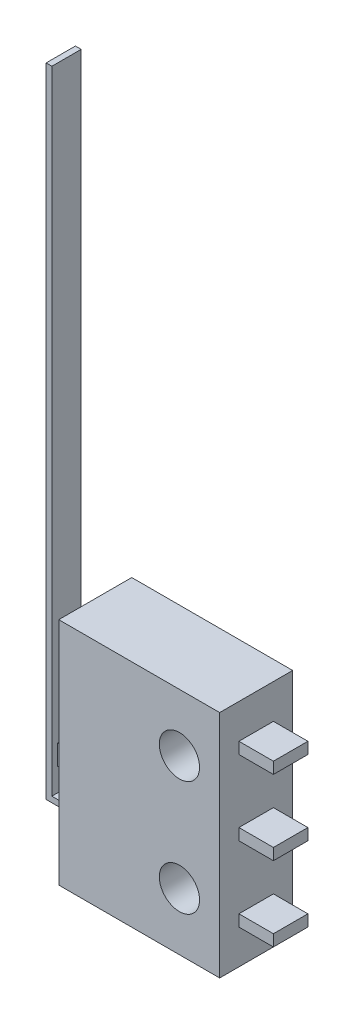
SolidWorks part; units mm, degrees
ref_plane "Front Plane" through (0, 0, 0) normal (0, 0, 1) x (1, 0, 0)
ref_plane "Top Plane" through (0, 0, 0) normal (0, 1, 0) x (1, 0, 0)
ref_plane "Right Plane" through (0, 0, 0) normal (1, 0, 0) x (0, 0, -1)
sketch "Sketch1" plane through (0, 0, 0) normal (0, 0, 1) x (1, 0, 0)
  line L1 (0, 0) -> (14, 0)
  line L2 (0, 0) -> (0, 20)
  line L3 (0, 20) -> (14, 20)
  line L4 (14, 0) -> (14, 20)
  dimension "D1" = 14
  dimension "D2" = 20
extrude "Boss-Extrude1" add sketch "Sketch1" against normal blind 6.35
sketch "Sketch2" plane through (0, 0, 0) normal (-1, 0, 0) x (0, 0, 1)
  line L0 (-6.35, 7) -> (0, 7) construction
  line L1 (-6.35, 20) -> (-6.35, 0) construction
  line L2 (0, 20) -> (0, 0) construction
  line L3 (-6.35, 0) -> (0, 0) construction
  line L5 (-4.45, 7) -> (-1.9, 7)
  line L6 (-4.45, 7) -> (-4.45, 8.7542)
  line L7 (-4.45, 8.7542) -> (-1.9, 8.7542)
  line L8 (-1.9, 7) -> (-1.9, 8.7542)
  dimension "D1" = 7
  dimension "D2" = 1.9
  dimension "D3" = 1.9
  dimension "D4" = 1.7542
extrude "Boss-Extrude2" add sketch "Sketch2" along normal blind 2
sketch "Sketch3" plane through (0, 0, 0) normal (-1, 0, 0) x (0, 0, 1)
  line L0 (-6.35, 4) -> (0, 4) construction
  line L1 (-6.35, 20) -> (-6.35, 0) construction
  line L2 (0, 20) -> (0, 0) construction
  line L3 (-6.35, 0) -> (0, 0) construction
  line L5 (-4.45, 4) -> (-1.9, 4)
  line L6 (-4.45, 4) -> (-4.45, 4.5)
  line L7 (-4.45, 4.5) -> (-1.9, 4.5)
  line L8 (-1.9, 4) -> (-1.9, 4.5)
  dimension "D1" = 4
  dimension "D2" = 1.9
  dimension "D3" = 1.9
  dimension "D4" = 0.5
extrude "Boss-Extrude3" add sketch "Sketch3" along normal blind 3
sketch "Sketch4" plane through (0, 4.5, 0) normal (0, 1, 0) x (1, 0, 0)
  line L0 (-3, 1.9) -> (0, 1.9) construction
  line L1 (-3, 4.45) -> (-2.5, 4.45)
  line L2 (-3, 4.45) -> (-3, 1.9)
  line L3 (-3, 1.9) -> (-2.5, 1.9)
  line L4 (-2.5, 4.45) -> (-2.5, 1.9)
  dimension "D1" = 0.5
extrude "Boss-Extrude4" add sketch "Sketch4" along normal blind 55
sketch "Sketch5" plane through (14, 0, 0) normal (1, 0, 0) x (0, 0, -1)
  line L0 (3.175, 20) -> (3.175, 0) construction
  line L1 (6.35, 20) -> (0, 20) construction
  line L2 (6.35, 0) -> (0, 0) construction
  line L4 (1.675, 4) -> (4.675, 4)
  line L5 (1.675, 4) -> (1.675, 3)
  line L6 (1.675, 3) -> (4.675, 3)
  line L7 (4.675, 4) -> (4.675, 3)
  line L8 (1.675, 4) -> (4.675, 3) construction
  line L9 (1.675, 3) -> (4.675, 4) construction
  line L10 (1.675, 10.5) -> (4.675, 10.5)
  line L11 (1.675, 10.5) -> (1.675, 9.5)
  line L12 (1.675, 9.5) -> (4.675, 9.5)
  line L13 (4.675, 10.5) -> (4.675, 9.5)
  line L14 (1.675, 10.5) -> (4.675, 9.5) construction
  line L15 (1.675, 9.5) -> (4.675, 10.5) construction
  line L16 (1.675, 17) -> (4.675, 17)
  line L17 (1.675, 17) -> (1.675, 16)
  line L18 (1.675, 16) -> (4.675, 16)
  line L19 (4.675, 17) -> (4.675, 16)
  line L20 (1.675, 17) -> (4.675, 16) construction
  line L21 (1.675, 16) -> (4.675, 17) construction
  point P6 (3.175, 3.5)
  point P11 (3.175, 10)
  point P16 (3.175, 16.5)
  point P21 (3.175, 10)
  dimension "D1" = 1
  dimension "D2" = 1
  dimension "D3" = 1
  dimension "D4" = 3
  dimension "D5" = 3
  dimension "D6" = 3
  dimension "D7" = 3
  dimension "D8" = 3
extrude "Boss-Extrude5" add sketch "Sketch5" along normal blind 3
hole_wizard "Ø3.0mm Dowel Hole1" positions "3DSketch1" profile "Sketch6" hole size "Ø3.0" standard "ANSI Metric" end condition through all
sketch3d "3DSketch1"
  line L0 (10.5, 20, 0) -> (10.5, 0, 0) construction
  line L1 (14, 20, 0) -> (0, 20, 0) construction
  line L2 (0, 0, 0) -> (14, 0, 0) construction
  line L4 (14, 0, 0) -> (14, 20, 0) construction
  line L5 (10.5, 15, 0) -> (14, 15, 0) construction
  line L7 (10.5, 5, 0) -> (14, 5, 0) construction
  point P0 (10.5, 15, 0)
  point P2 (10.5, 5, 0)
  point P22 (10.5, 5, 0)
  point P23 (0, 0, 0)
  dimension "D1" = 3.5
  dimension "D2" = 10
  dimension "D3" = 5
  dimension "D4" = 5
sketch "Sketch6" plane through (10.5, 15, 0) normal (1, 0, 0) x (0, -1, 0)
  line L0 (0, 0) -> (0, 6.35)
  line L1 (0, 6.35) -> (1.75, 6.35)
  line L2 (1.75, 6.35) -> (1.75, 0)
  line L5 (1.75, 0) -> (0, 0)
  line L11 (0, -6.35) -> (0, 107.95) construction
  dimension "Thru Hole Dia." = 3.5
  dimension "Thru Hole Depth" = 6.35
